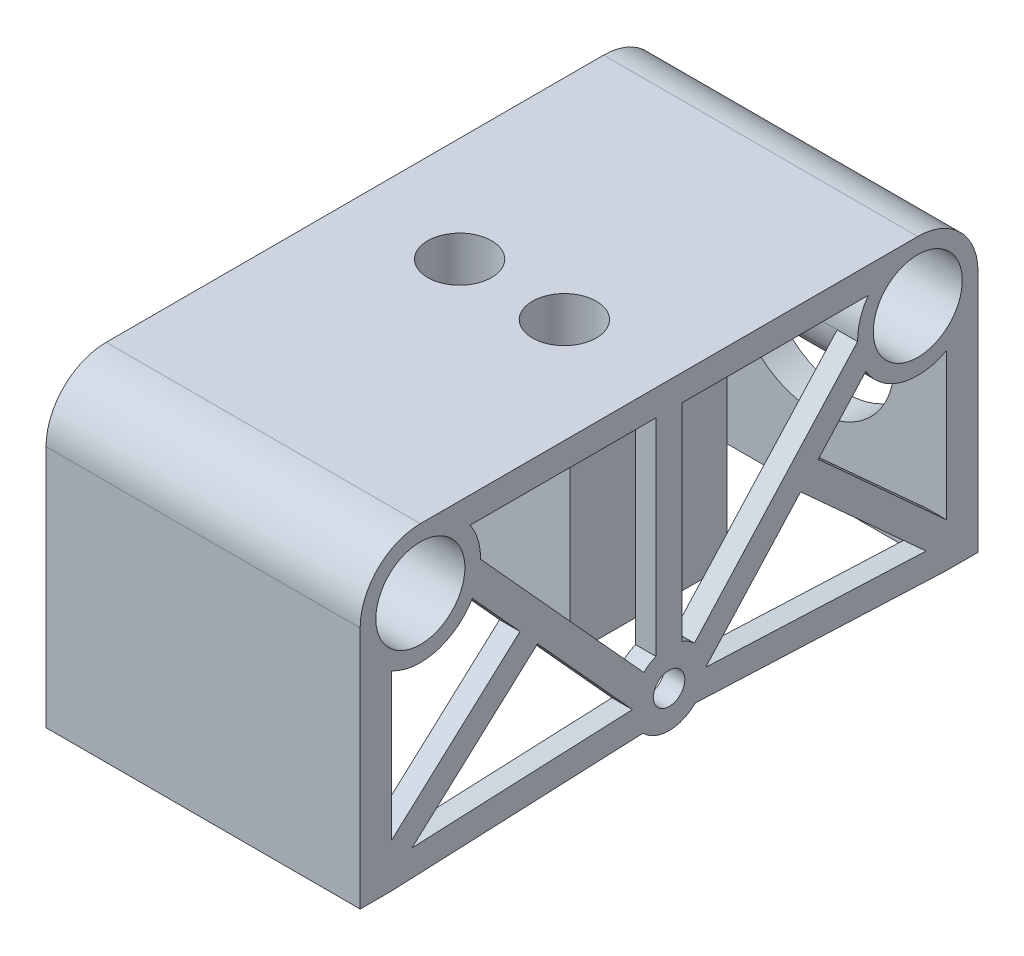
SolidWorks part; units mm, degrees
ref_plane "Front Plane" through (0, 0, 0) normal (0, 0, 1) x (1, 0, 0)
ref_plane "Top Plane" through (0, 0, 0) normal (0, 1, 0) x (1, 0, 0)
ref_plane "Right Plane" through (0, 0, 0) normal (1, 0, 0) x (0, 0, -1)
sketch "Sketch4" plane through (0, 0, 0) normal (0, 0, 1) x (1, 0, 0)
  line L0 (-30, 29) -> (-30, -29)
  line L1 (-30, -29) -> (30, -29)
  line L2 (30, -29) -> (30, 29)
  line L3 (30, 29) -> (-30, 29)
  point P4 (30, 0)
  point P5 (0, 29)
  dimension "D1" = 58
  dimension "D2" = 60
extrude "Boss-Extrude2" add sketch "Sketch4" along normal mid plane 118
sketch "Sketch5" plane through (30, 0, 0) normal (1, 0, 0) x (0, 0, -1)
  line L0 (-7.1278, -22) -> (-53.0521, -25.7381) construction
  line L1 (-53.0521, -30.7546) -> (-5.035, -26.8462) construction
  line L2 (-39.0141, 14.8656) -> (-7.1278, -22) construction
  line L3 (-53.0521, -30.7546) -> (-53.0521, 7.429) construction
  line L6 (-36.121, 19.1639) -> (-4.8602, -16.9785)
  line L8 (-38.0132, 24) -> (-2.4867, 24)
  line L10 (0, -22) -> (0, 29) construction
  line L11 (-2.4867, 24) -> (-2.4867, -15.4691)
  line L29 (0, 0) -> (0, 42.8689) construction
  line L30 (-59, 29) -> (59, 29) construction
  line L31 (-59, -29) -> (-59, 29) construction
  line L32 (-48.8335, -25.3947) -> (-23.2963, -3.3067) construction
  line L33 (-26.5672, 0.475) -> (-53.0521, -22.4327)
  line L34 (-43.6385, -14.2906) -> (-40.3676, -18.0723) construction
  line L35 (-42.0031, -16.1814) -> (-53.0521, -25.7381) construction
  line L36 (-26.5672, 0.475) -> (-37.0815, 12.6313)
  line L37 (-53.0521, 7.429) -> (-53.0521, -22.4327)
  line L38 (-23.2963, -3.3067) -> (-48.8335, -25.3947)
  line L39 (-48.8335, -25.3947) -> (-7.1278, -22)
  line L40 (-7.1278, -22) -> (-23.2963, -3.3067)
  line L41 (-5.035, -26.8462) -> (-53.0521, -30.7546)
  line L42 (-53.0521, -30.7546) -> (53.0521, -30.7546)
  line L43 (5.035, -26.8462) -> (53.0521, -30.7546)
  line L44 (38.0132, 24) -> (2.4867, 24)
  line L45 (2.4867, 24) -> (2.4867, -15.4691)
  line L46 (36.121, 19.1639) -> (4.8602, -16.9785)
  line L47 (48.8335, -25.3947) -> (7.1278, -22)
  line L48 (23.2963, -3.3067) -> (48.8335, -25.3947)
  line L49 (7.1278, -22) -> (23.2963, -3.3067)
  line L50 (26.5672, 0.475) -> (37.0815, 12.6313)
  line L51 (26.5672, 0.475) -> (53.0521, -22.4327)
  line L52 (53.0521, 7.429) -> (53.0521, -22.4327)
  line L53 (-47.5, 17.5) -> (0, 17.5) construction
  line L54 (0, 17.5) -> (0, -22) construction
  circle A8 centre (-47.5, 17.5) radius 8.5
  circle A9 centre (-47.5, 17.5) radius 11.5
  circle A10 centre (47.5, 17.5) radius 8.5
  circle A11 centre (47.5, 17.5) radius 11.5
  circle A12 centre (0, -22) radius 3
  arc A13 (-53.0521, 7.429) -> (-37.0815, 12.6313) centre (-47.5, 17.5) ccw
  arc A14 (-5.035, -26.8462) -> (5.035, -26.8462) centre (0, -22) ccw
  arc A15 (-38.0132, 24) -> (-36.121, 19.1639) centre (-47.5, 17.5) cw
  arc A16 (2.4867, -15.4691) -> (4.8602, -16.9785) centre (0, -22) cw
  arc A17 (-2.4867, -15.4691) -> (-4.8602, -16.9785) centre (0, -22) ccw
  arc A18 (38.0132, 24) -> (36.121, 19.1639) centre (47.5, 17.5) ccw
  arc A19 (53.0521, 7.429) -> (37.0815, 12.6313) centre (47.5, 17.5) cw
  point P3 (-47.5, 17.5)
  point P18 (0, -30.7546)
  point P27 (-42.0031, -16.1814)
  point P58 (59, 17.5)
  dimension "D1" = 17
  dimension "D4" = 6
  dimension "D3" = 5
  dimension "D5" = 39.5
  dimension "D6" = 5
  dimension "D7" = 5
  dimension "D2" = 3
sketch "Sketch6" plane through (-30, 0, 0) normal (-1, 0, 0) x (0, 0, 1)
  line L0 (0, -6.9366) -> (0, 49.2251) construction
  line L1 (0, -22) -> (0, 29) construction
  line L2 (-7, -22) -> (-53, -23.9953) construction
  line L3 (-53, -29) -> (-4.9821, -26.9172) construction
  line L4 (-39.7346, 14.0434) -> (-7, -22) construction
  line L5 (-53, -29) -> (-53, 7.4005) construction
  line L8 (-36.0007, 17.3692) -> (-4.8392, -16.9421)
  line L10 (-38.0132, 24) -> (-2.5, 24)
  line L12 (0, -22) -> (0, 29) construction
  line L13 (-2.5, 24) -> (-2.5, -15.4617)
  line L31 (-49.095, -23.8259) -> (-25.1183, -2.0503) construction
  line L32 (-28.4798, 1.651) -> (-53, -20.6182)
  line L33 (-43.8665, -12.3231) -> (-40.505, -16.0245) construction
  line L34 (-42.1857, -14.1738) -> (-53, -23.9953) construction
  line L35 (-28.4798, 1.651) -> (-37.5841, 11.6756)
  line L36 (-53, 7.4005) -> (-53, -20.6182)
  line L37 (-25.1183, -2.0503) -> (-49.095, -23.8259)
  line L38 (-49.095, -23.8259) -> (-7, -22)
  line L39 (-7, -22) -> (-25.1183, -2.0503)
  line L40 (-4.9821, -26.9172) -> (-53, -29)
  line L42 (4.9821, -26.9172) -> (53, -29)
  line L43 (38.0132, 24) -> (2.5, 24)
  line L44 (2.5, 24) -> (2.5, -15.4617)
  line L45 (36.0007, 17.3692) -> (4.8392, -16.9421)
  line L46 (49.095, -23.8259) -> (7, -22)
  line L47 (25.1182, -2.0503) -> (49.095, -23.8259)
  line L48 (7, -22) -> (25.1182, -2.0503)
  line L49 (28.4798, 1.651) -> (37.584, 11.6756)
  line L50 (28.4798, 1.651) -> (53, -20.6182)
  line L51 (53, 7.4005) -> (53, -20.6182)
  line L52 (-53, -29) -> (-53, -39.7033)
  line L53 (-53, -39.7033) -> (53, -37.9369)
  line L54 (53, -37.9369) -> (53, -29)
  line L55 (-47.5, 29) -> (-47.5, 35.7267)
  line L56 (-47.5, 35.7267) -> (-66.8543, 35.7267)
  line L57 (-66.8543, 35.7267) -> (-66.1473, 17.5)
  line L58 (-66.1473, 17.5) -> (-59, 17.5)
  line L59 (47.5, 29) -> (47.0761, 34.9367)
  line L60 (47.0761, 34.9367) -> (67.1714, 34.5747)
  line L61 (67.1714, 34.5747) -> (67.1714, 17.5)
  line L62 (67.1714, 17.5) -> (59, 17.5)
  circle A0 centre (-47.5, 17.5) radius 8.5
  arc A1 (-47.5, 29) -> (-59, 17.5) centre (-47.5, 17.5) ccw
  circle A10 centre (0, -22) radius 3
  arc A11 (-53, 7.4005) -> (-37.5841, 11.6756) centre (-47.5, 17.5) ccw
  arc A12 (-4.9821, -26.9172) -> (4.9821, -26.9172) centre (0, -22) ccw
  arc A13 (-38.0132, 24) -> (-36.0007, 17.3692) centre (-47.5, 17.5) cw
  arc A14 (2.5, -15.4617) -> (4.8392, -16.9421) centre (0, -22) cw
  arc A15 (-2.5, -15.4617) -> (-4.8392, -16.9421) centre (0, -22) ccw
  arc A16 (38.0132, 24) -> (36.0007, 17.3692) centre (47.5, 17.5) ccw
  arc A17 (53, 7.4005) -> (37.584, 11.6756) centre (47.5, 17.5) cw
  circle A18 centre (47.5, 17.5) radius 8.5
  circle A19 centre (-47.5, 17.5) radius 11.5 construction
  arc A20 (-53, 7.4005) -> (-38.0132, 24) centre (-47.5, 17.5) ccw
  arc A21 (37.0273, 22.251) -> (38.0132, 24) centre (47.5, 17.5) cw
  arc A22 (47.5, 29) -> (59, 17.5) centre (47.5, 17.5) cw
  arc A23 (53, 7.4005) -> (51.5815, 6.7487) centre (47.5, 17.5) cw
  point P13 (-47.5, 17.5)
  point P28 (0, -29)
  point P37 (-42.1857, -14.1738)
  line M23 (-59, 29) -> (-59, -29)
  line M24 (-59, -29) -> (59, -29)
  line M25 (59, -29) -> (59, 29)
  line M26 (59, 29) -> (-59, 29)
  dimension "D2" = 17
  dimension "D1" = 3
extrude "Cut-Extrude2" cut sketch "Sketch6" against normal through all contours L57 L58 L55 L56 M23 M26 | A1 M26 M23 | A0 | A15 L13 L10 A13 L8 | A20 L36 L32 L35 | L38 L39 L37 | A12 L40 M24 | A12 L42 M24 | A10 | A16 L43 L44 A14 L45 | L48 L46 L47 | L51 A17 L49 L50 | A18 | L62 L61 L60 L59 M26 M25 | A22 M26 M25
sketch "Sketch7" plane through (-30, 0, 0) normal (-1, 0, 0) x (0, 0, 1)
  line L9 (-15, 24) -> (-15, -11)
  line L10 (-38.0132, 24) -> (-2.5, 24) construction
  line L11 (-15, -11) -> (15.389, -11)
  line L12 (15.389, -11) -> (15, 24)
  line L14 (15, 24) -> (-15, 24)
  line L15 (47.5, 29) -> (-47.5, 29) construction
  point P5 (0, 24)
  dimension "D1" = 30
  dimension "D2" = 40
extrude "Boss-Extrude3" add sketch "Sketch7" along normal mid plane 52.2 from surface at -30 starting at plane "Right Plane"
sketch "Sketch8" plane through (-26.1, 0, 0) normal (-1, 0, 0) x (0, 0, 1)
  line L0 (-15, 24) -> (-38.0132, 24)
  line L1 (0, 0) -> (0, 26.1631) construction
  line L2 (-15, 24) -> (-15, -11)
  line L3 (-53, 7.4005) -> (-53, -24.0111)
  line L8 (-15, -11) -> (-14.2011, -11)
  line L10 (53, 7.4005) -> (53, -24.0111)
  line L15 (15, 24) -> (15, -11)
  line L16 (15, 24) -> (38.0132, 24)
  line L17 (-14.2011, -11) -> (15, -11)
  line L18 (-53, -24.0111) -> (-53, -39.4582)
  line L19 (-53, -39.4582) -> (53, -37.6121)
  line L20 (53, -37.6121) -> (53, -24.0111)
  arc A1 (-53, 7.4005) -> (-38.0132, 24) centre (-47.5, 17.5) ccw
  arc A7 (38.0132, 24) -> (53, 7.4005) centre (47.5, 17.5) ccw
  point P37 (47.5, 17.5)
extrude "Cut-Extrude7" cut sketch "Sketch8" against normal up to surface (52.2 mm away) contours A7 L10 L20 L19 L18 L3 A1 L0 L2 L8 L17 L15 L16 up to face at (26.1, 4.1211, 9.1125)
sketch "Sketch9" plane through (0, 29, 0) normal (0, 1, 0) x (1, 0, 0)
  line L0 (30, 0) -> (-30, 0) construction
  line L3 (0, 0) -> (0, 34.2384) construction
  circle A0 centre (-10, 0) radius 6.1
  circle A1 centre (10, 0) radius 6.1
  point P4 (0, 0)
  dimension "D1" = 12.2
  dimension "D2" = 10
extrude "Cut-Extrude8" cut sketch "Sketch9" against normal through all
sketch "Sketch10" plane through (0, 0, -59) normal (0, 0, -1) x (-1, 0, 0)
  circle A0 centre (-4.7182, 0) radius 15.2902
extrude "Cut-Extrude9" cut sketch "Sketch10" against normal blind 10
